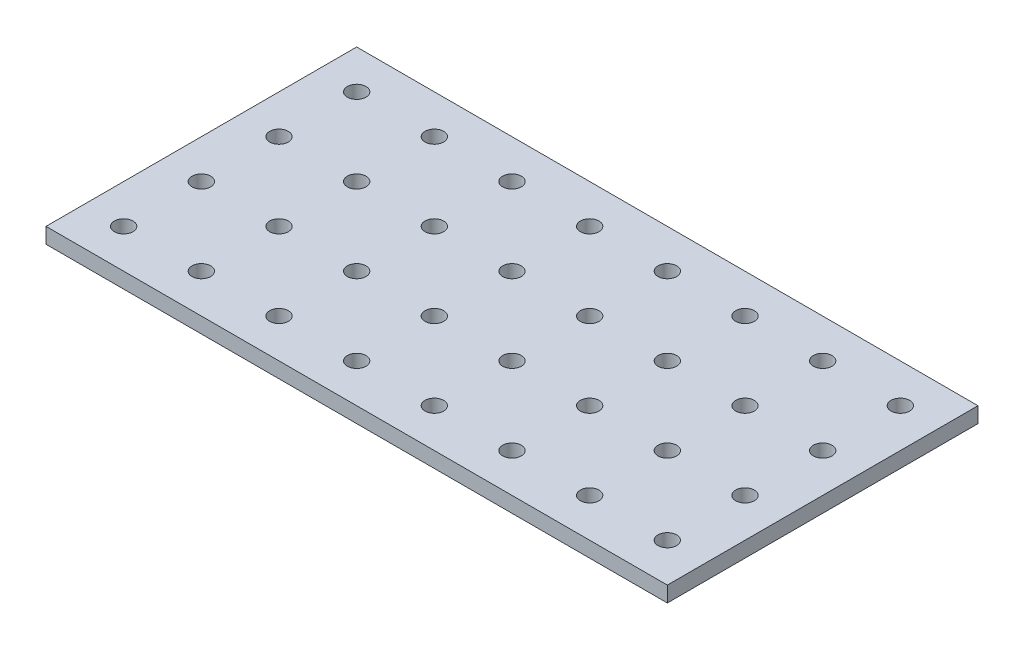
SolidWorks part; units mm, degrees
ref_plane "Front" through (0, 0, 0) normal (0, 0, 1) x (1, 0, 0)
ref_plane "Top" through (0, 0, 0) normal (0, 1, 0) x (1, 0, 0)
ref_plane "Right" through (0, 0, 0) normal (1, 0, 0) x (0, 0, -1)
sketch "草图1" plane through (0, 0, 0) normal (0, 1, 0) x (1, 0, 0)
  line L0 (-91.4106, -41.4106) -> (-91.4106, -16.4106) construction
  line L1 (-103.9106, -53.9106) -> (96.0894, -53.9106)
  line L2 (-103.9106, -53.9106) -> (-103.9106, 46.0894)
  line L3 (-103.9106, 46.0894) -> (96.0894, 46.0894)
  line L4 (96.0894, -53.9106) -> (96.0894, 46.0894)
  circle A0 centre (-91.4106, -41.4106) radius 3
  circle A1 centre (-66.4106, -41.4106) radius 3
  circle A2 centre (-41.4106, -41.4106) radius 3
  circle A3 centre (-16.4106, -41.4106) radius 3
  circle A4 centre (8.5894, -41.4106) radius 3
  circle A5 centre (33.5894, -41.4106) radius 3
  circle A6 centre (58.5894, -41.4106) radius 3
  circle A7 centre (83.5894, -41.4106) radius 3
  circle A20 centre (-66.4106, -16.4106) radius 3
  circle A21 centre (-41.4106, -16.4106) radius 3
  circle A22 centre (-16.4106, -16.4106) radius 3
  circle A23 centre (8.5894, -16.4106) radius 3
  circle A24 centre (33.5894, -16.4106) radius 3
  circle A25 centre (58.5894, -16.4106) radius 3
  circle A26 centre (83.5894, -16.4106) radius 3
  circle A39 centre (-66.4106, 8.5894) radius 3
  circle A40 centre (-41.4106, 8.5894) radius 3
  circle A41 centre (-16.4106, 8.5894) radius 3
  circle A42 centre (8.5894, 8.5894) radius 3
  circle A43 centre (33.5894, 8.5894) radius 3
  circle A44 centre (58.5894, 8.5894) radius 3
  circle A45 centre (83.5894, 8.5894) radius 3
  circle A58 centre (-66.4106, 33.5894) radius 3
  circle A59 centre (-41.4106, 33.5894) radius 3
  circle A60 centre (-16.4106, 33.5894) radius 3
  circle A61 centre (8.5894, 33.5894) radius 3
  circle A62 centre (33.5894, 33.5894) radius 3
  circle A63 centre (58.5894, 33.5894) radius 3
  circle A64 centre (83.5894, 33.5894) radius 3
  circle A77 centre (-91.4106, -16.4106) radius 3
  circle A78 centre (-91.4106, 8.5894) radius 3
  circle A79 centre (-91.4106, 33.5894) radius 3
  circle A80 centre (208.5894, -41.4106) radius 3 [skipped]
  circle A81 centre (233.5894, -41.4106) radius 3 [skipped]
  circle A82 centre (258.5894, -41.4106) radius 3 [skipped]
  circle A83 centre (283.5894, -41.4106) radius 3 [skipped]
  circle A84 centre (308.5894, -41.4106) radius 3 [skipped]
  circle A85 centre (333.5894, -41.4106) radius 3 [skipped]
  circle A86 centre (358.5894, -41.4106) radius 3 [skipped]
  circle A87 centre (383.5894, -41.4106) radius 3 [skipped]
  circle A88 centre (208.5894, -16.4106) radius 3 [skipped]
  circle A89 centre (233.5894, -16.4106) radius 3 [skipped]
  circle A90 centre (258.5894, -16.4106) radius 3 [skipped]
  circle A91 centre (283.5894, -16.4106) radius 3 [skipped]
  circle A92 centre (308.5894, -16.4106) radius 3 [skipped]
  circle A93 centre (333.5894, -16.4106) radius 3 [skipped]
  circle A94 centre (358.5894, -16.4106) radius 3 [skipped]
  circle A95 centre (383.5894, -16.4106) radius 3 [skipped]
  circle A96 centre (208.5894, 8.5894) radius 3 [skipped]
  circle A97 centre (233.5894, 8.5894) radius 3 [skipped]
  circle A98 centre (258.5894, 8.5894) radius 3 [skipped]
  circle A99 centre (283.5894, 8.5894) radius 3 [skipped]
  circle A100 centre (308.5894, 8.5894) radius 3 [skipped]
  circle A101 centre (333.5894, 8.5894) radius 3 [skipped]
  circle A102 centre (358.5894, 8.5894) radius 3 [skipped]
  circle A103 centre (383.5894, 8.5894) radius 3 [skipped]
  circle A104 centre (208.5894, 33.5894) radius 3 [skipped]
  circle A105 centre (233.5894, 33.5894) radius 3 [skipped]
  circle A106 centre (258.5894, 33.5894) radius 3 [skipped]
  circle A107 centre (283.5894, 33.5894) radius 3 [skipped]
  circle A108 centre (308.5894, 33.5894) radius 3 [skipped]
  circle A109 centre (333.5894, 33.5894) radius 3 [skipped]
  circle A110 centre (358.5894, 33.5894) radius 3 [skipped]
  circle A111 centre (383.5894, 33.5894) radius 3 [skipped]
  circle A112 centre (108.5894, -41.4106) radius 3 [skipped]
  circle A113 centre (133.5894, -41.4106) radius 3 [skipped]
  circle A114 centre (158.5894, -41.4106) radius 3 [skipped]
  circle A115 centre (183.5894, -41.4106) radius 3 [skipped]
  circle A116 centre (108.5894, -16.4106) radius 3 [skipped]
  circle A117 centre (133.5894, -16.4106) radius 3 [skipped]
  circle A118 centre (158.5894, -16.4106) radius 3 [skipped]
  circle A119 centre (183.5894, -16.4106) radius 3 [skipped]
  circle A120 centre (108.5894, 8.5894) radius 3 [skipped]
  circle A121 centre (133.5894, 8.5894) radius 3 [skipped]
  circle A122 centre (158.5894, 8.5894) radius 3 [skipped]
  circle A123 centre (183.5894, 8.5894) radius 3 [skipped]
  circle A124 centre (108.5894, 33.5894) radius 3 [skipped]
  circle A125 centre (133.5894, 33.5894) radius 3 [skipped]
  circle A126 centre (158.5894, 33.5894) radius 3 [skipped]
  circle A127 centre (183.5894, 33.5894) radius 3 [skipped]
  dimension "D3" = 6
  dimension "D4" = 12.5
  dimension "D5" = 12.5
  dimension "D1" = 100
  dimension "D2" = 200
  dimension "D8" = 25
  dimension "D6" = 20
  dimension "D7" = 4
extrude "凸台-拉伸1" add sketch "草图1" along normal blind 5 contours A0
